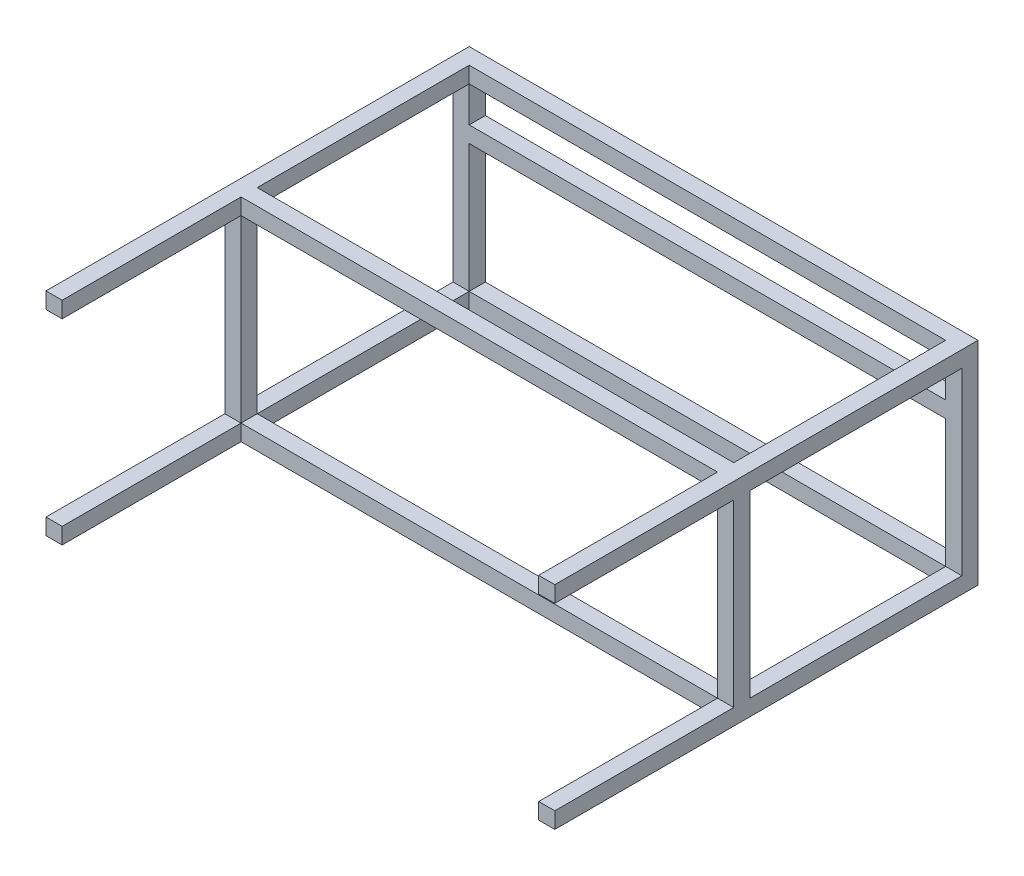
SolidWorks part; units mm, degrees
ref_plane "Alzado" through (0, 0, 0) normal (0, 0, 1) x (1, 0, 0)
ref_plane "Planta" through (0, 0, 0) normal (0, 1, 0) x (1, 0, 0)
ref_plane "Vista lateral" through (0, 0, 0) normal (1, 0, 0) x (0, 0, -1)
sketch "Croquis1" plane through (0, 0, 0) normal (0, 0, 1) x (1, 0, 0)
  line L1 (-600, 250) -> (600, 250)
  line L2 (-600, 250) -> (-600, -250)
  line L3 (-600, -250) -> (600, -250)
  line L4 (600, 250) -> (600, -250)
  line L5 (-600, 250) -> (600, -250) construction
  line L6 (-600, -250) -> (600, 250) construction
  line L7 (-561.9, 211.9) -> (561.9, 211.9)
  line L8 (-561.9, 211.9) -> (-561.9, -211.9)
  line L9 (-561.9, -211.9) -> (561.9, -211.9)
  line L10 (561.9, 211.9) -> (561.9, -211.9)
  line L11 (-561.9, 211.9) -> (561.9, -211.9) construction
  line L12 (-561.9, -211.9) -> (561.9, 211.9) construction
  point P0 (0, 0)
  point P6 (0, 0)
  dimension "D1" = 1200
  dimension "D2" = 500
  dimension "D3" = 38.1
  dimension "D4" = 38.1
extrude "Saliente-Extruir1" add sketch "Croquis1" along normal blind 38.1
sketch "Croquis2" plane through (0, 0, 38.1) normal (0, 0, 1) x (1, 0, 0)
  line L1 (-600, 250) -> (-561.9, 250)
  line L2 (-600, 250) -> (-600, 211.9)
  line L3 (-600, 211.9) -> (-561.9, 211.9)
  line L4 (-561.9, 250) -> (-561.9, 211.9)
  line L5 (-600, -250) -> (-561.9, -250)
  line L6 (-600, -250) -> (-600, -211.9)
  line L7 (-600, -211.9) -> (-561.9, -211.9)
  line L8 (-561.9, -250) -> (-561.9, -211.9)
  line L9 (600, 250) -> (561.9, 250)
  line L10 (600, 250) -> (600, 211.9)
  line L11 (600, 211.9) -> (561.9, 211.9)
  line L12 (561.9, 250) -> (561.9, 211.9)
  line L13 (600, -250) -> (561.9, -250)
  line L14 (600, -250) -> (600, -211.9)
  line L15 (600, -211.9) -> (561.9, -211.9)
  line L16 (561.9, -250) -> (561.9, -211.9)
extrude "Saliente-Extruir2" add sketch "Croquis2" along normal blind 960
sketch "Croquis3" plane through (0, 0, 0) normal (0, 0, -1) x (-1, 0, 0)
  line L0 (-561.9, -211.9) -> (-561.9, 211.9) construction
  line L1 (-561.9, 90) -> (561.9, 90)
  line L2 (-561.9, 90) -> (-561.9, 128.1)
  line L3 (-561.9, 128.1) -> (561.9, 128.1)
  line L4 (561.9, 90) -> (561.9, 128.1)
  line L5 (561.9, 211.9) -> (561.9, -211.9) construction
  line L9 (600, -250) -> (-600, -250) construction
  dimension "D1" = 38.1
  dimension "D2" = 340
extrude "Saliente-Extruir4" add sketch "Croquis3" against normal blind 38.1
sketch "Croquis4" plane through (0, -250, 0) normal (0, -1, 0) x (1, 0, 0)
  line L0 (-561.9, 998.1) -> (-561.9, 38.1) construction
  line L1 (-561.9, 576.2) -> (561.9, 576.2)
  line L2 (-561.9, 576.2) -> (-561.9, 538.1)
  line L3 (-561.9, 538.1) -> (561.9, 538.1)
  line L4 (561.9, 576.2) -> (561.9, 538.1)
  line L5 (561.9, 998.1) -> (561.9, 38.1) construction
  line L6 (-561.9, 38.1) -> (561.9, 38.1) construction
  dimension "D1" = 38.1
  dimension "D2" = 500
extrude "Saliente-Extruir5" add sketch "Croquis4" against normal blind 38.1
sketch "Croquis5" plane through (0, 250, 0) normal (0, 1, 0) x (1, 0, 0)
  line L1 (-561.9, -538.1) -> (561.9, -538.1)
  line L2 (-561.9, -538.1) -> (-561.9, -576.2)
  line L3 (-561.9, -576.2) -> (561.9, -576.2)
  line L4 (561.9, -538.1) -> (561.9, -576.2)
extrude "Saliente-Extruir6" add sketch "Croquis5" against normal blind 38.1
sketch "Croquis6" plane through (-600, 0, 0) normal (-1, 0, 0) x (0, 0, 1)
  line L0 (998.1, -211.9) -> (38.1, -211.9) construction
  line L1 (538.1, -211.9) -> (576.2, -211.9)
  line L2 (538.1, -211.9) -> (538.1, 211.9)
  line L3 (538.1, 211.9) -> (576.2, 211.9)
  line L4 (576.2, -211.9) -> (576.2, 211.9)
  line L5 (998.1, 211.9) -> (38.1, 211.9) construction
  line L6 (38.1, 211.9) -> (38.1, -211.9) construction
  dimension "D1" = 500
  dimension "D2" = 38.1
extrude "Saliente-Extruir7" add sketch "Croquis6" against normal blind 38.1
sketch "Croquis7" plane through (600, 0, 0) normal (1, 0, 0) x (0, 0, -1)
  line L1 (-576.2, -211.9) -> (-538.1, -211.9)
  line L2 (-576.2, -211.9) -> (-576.2, 211.9)
  line L3 (-576.2, 211.9) -> (-538.1, 211.9)
  line L4 (-538.1, -211.9) -> (-538.1, 211.9)
extrude "Saliente-Extruir8" add sketch "Croquis7" against normal blind 38.1
